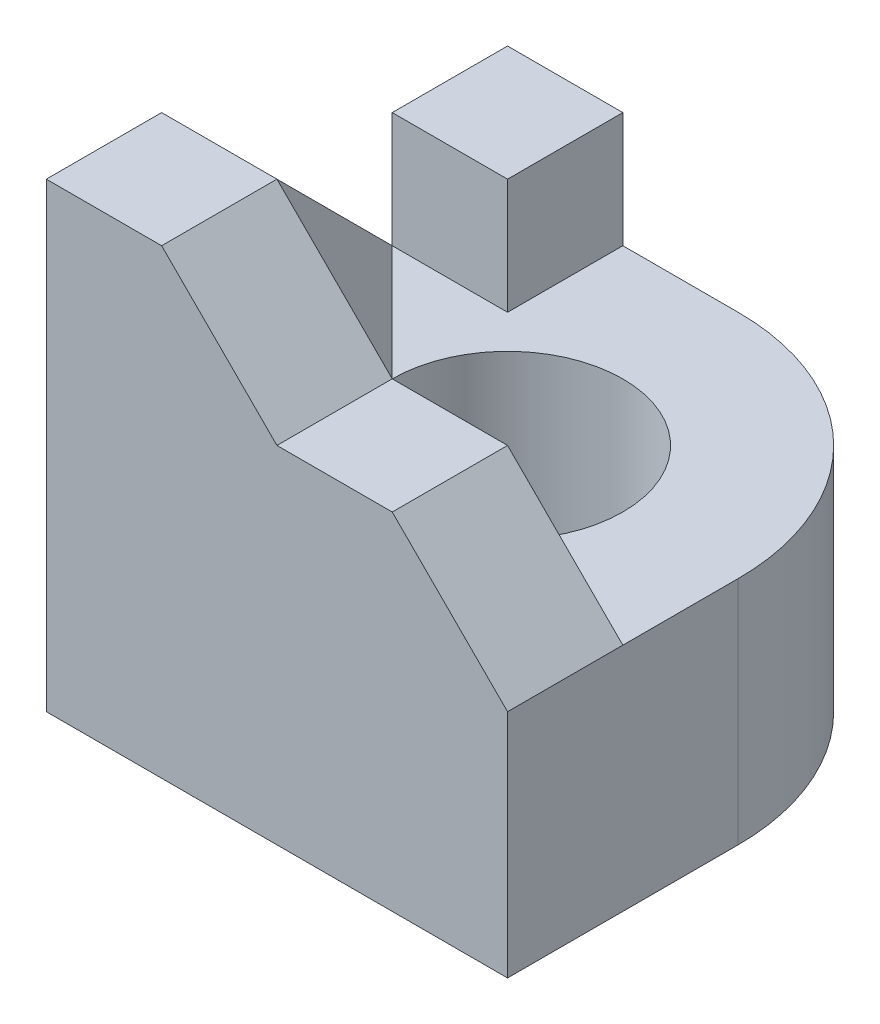
SolidWorks part; units mm, degrees
material "6061 Alloy"
ref_plane "Front Plane" through (0, 0, 0) normal (0, 0, 1) x (1, 0, 0)
ref_plane "Top Plane" through (0, 0, 0) normal (0, 1, 0) x (1, 0, 0)
ref_plane "Right Plane" through (0, 0, 0) normal (1, 0, 0) x (0, 0, -1)
sketch "Sketch1" plane through (0, 0, 0) normal (0, 1, 0) x (1, 0, 0)
  line L0 (-20, 0) -> (20, 0) construction
  line L1 (0, -20) -> (0, 20) construction
  line L2 (-20, -20) -> (-20, 20)
  line L3 (-20, 20) -> (0, 20)
  line L4 (-20, -20) -> (20, -20)
  line L5 (20, -20) -> (20, 0)
  arc A0 (20, 0) -> (0, 20) centre (0, 0) ccw
  circle A1 centre (0, 0) radius 10
  point P4 (0, 0)
  point P8 (0, 0)
  dimension "D3" = 20
  dimension "D1" = 40
  dimension "D2" = 40
extrude "Boss-Extrude1" add sketch "Sketch1" along normal blind 20
sketch "Sketch3" plane through (-20, 0, 0) normal (-1, 0, 0) x (0, 0, 1)
  line L0 (-20, 20) -> (-20, 30)
  line L1 (-20, 30) -> (-10, 30)
  line L2 (-10, 30) -> (-10, 20)
  line L3 (-10, 20) -> (-20, 20)
  line L4 (20, 20) -> (20, 40)
  line L5 (20, 40) -> (10, 40)
  line L6 (10, 40) -> (0, 30)
  line L7 (0, 30) -> (0, 20)
  line L8 (0, 20) -> (20, 20)
  dimension "D1" = 10
  dimension "D2" = 10
  dimension "D3" = 45
  dimension "D4" = 10
  dimension "D5" = 20
extrude "Boss-Extrude2" add sketch "Sketch3" against normal blind 10
sketch "Sketch4" plane through (0, 0, 20) normal (0, 0, 1) x (1, 0, 0)
  line L0 (-10, 40) -> (0, 30)
  line L1 (0, 30) -> (10, 30)
  line L2 (10, 30) -> (20, 20)
  line L3 (20, 20) -> (-10, 20)
  line L4 (-10, 20) -> (-10, 40)
  dimension "D1" = 10
  dimension "D2" = 10
  dimension "D3" = 10
extrude "Boss-Extrude3" add sketch "Sketch4" against normal blind 10
